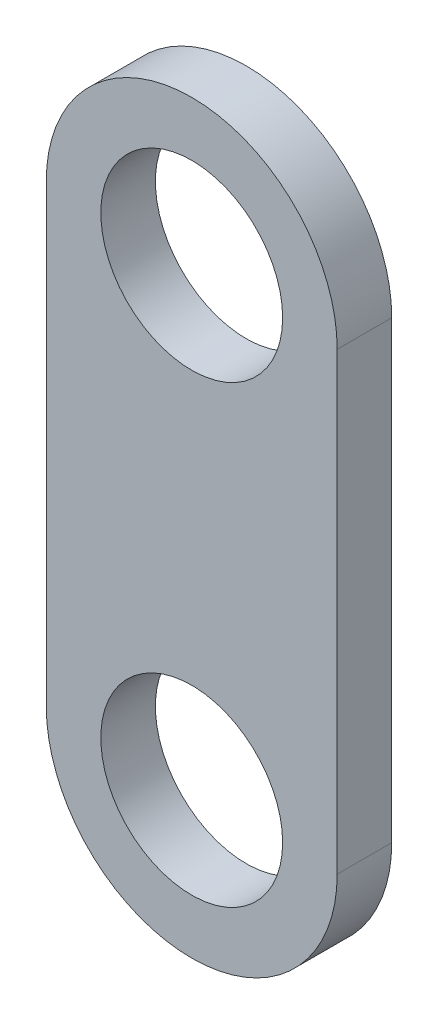
SolidWorks part; units mm, degrees
ref_plane "前基準面" through (0, 0, 0) normal (0, 0, 1) x (1, 0, 0)
ref_plane "上基準面" through (0, 0, 0) normal (0, 1, 0) x (1, 0, 0)
ref_plane "右基準面" through (0, 0, 0) normal (1, 0, 0) x (0, 0, -1)
sketch "草圖1" plane through (0, 0, 0) normal (0, 0, 1) x (1, 0, 0)
  line L0 (0, -1.25) -> (0, 1.25) construction
  line L1 (-0.8, -1.25) -> (-0.8, 1.25)
  line L2 (0.8, -1.25) -> (0.8, 1.25)
  arc A0 (-0.8, -1.25) -> (0.8, -1.25) centre (0, -1.25) ccw
  arc A1 (0.8, 1.25) -> (-0.8, 1.25) centre (0, 1.25) ccw
  circle A2 centre (0, 1.25) radius 0.5
  circle A3 centre (0, -1.25) radius 0.5
  point P2 (0, 0)
  dimension "D1" = 1
  dimension "D2" = 0.8
  dimension "D4" = 1
  dimension "D3" = 2.5
extrude "填料-伸長1" add sketch "草圖1" along normal blind 0.3
